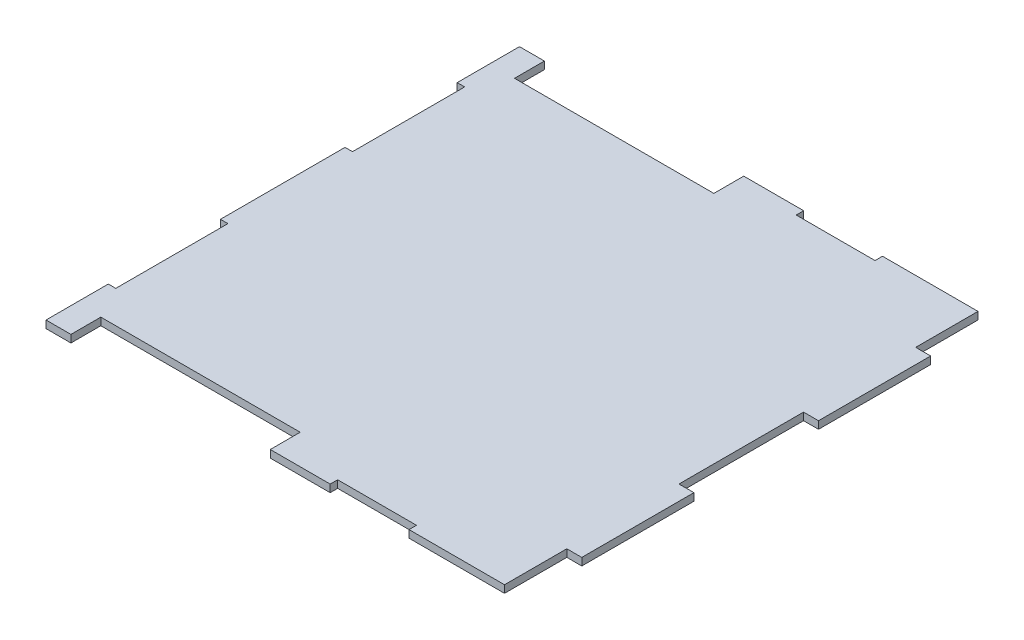
SolidWorks part; units mm, degrees
ref_plane "Front Plane" through (0, 0, 0) normal (0, 0, 1) x (1, 0, 0)
ref_plane "Top Plane" through (0, 0, 0) normal (0, 1, 0) x (1, 0, 0)
ref_plane "Right Plane" through (0, 0, 0) normal (1, 0, 0) x (0, 0, -1)
sketch "Sketch1" plane through (0, 0, 0) normal (0, 1, 0) x (1, 0, 0)
  line L1 (-95, -95) -> (95, -95)
  line L2 (-95, -95) -> (-95, 95)
  line L3 (-95, 95) -> (95, 95)
  line L4 (95, -95) -> (95, 95)
  line L5 (-95, -95) -> (95, 95) construction
  line L6 (-95, 95) -> (95, -95) construction
  point P0 (0, 0)
  dimension "D1" = 190
  dimension "D2" = 190
extrude "Boss-Extrude1" add sketch "Sketch1" along normal blind 3
sketch "Sketch2" plane through (0, 3, 0) normal (0, 1, 0) x (1, 0, 0)
  line L0 (-95, -95) -> (-95, -70)
  line L1 (-95, 95) -> (-95, -95) construction
  line L2 (-95, -70) -> (-92, -70)
  line L3 (-92, -70) -> (-92, -25)
  line L4 (-92, -25) -> (-95, -25)
  line L5 (-95, -25) -> (-95, 25)
  line L6 (89, 95) -> (89, 70)
  line L7 (-92, 25) -> (-95, 25)
  line L8 (-92, 70) -> (-92, 25)
  line L9 (-95, 70) -> (-92, 70)
  line L10 (-95, 95) -> (-95, 70)
  line L11 (0, -1000) -> (0, 49000) construction
  line L21 (-95, -95) -> (89, -95)
  line L22 (-95, 95) -> (89, 95)
  line L23 (89, 70) -> (95, 70)
  line L24 (95, -95) -> (95, 95) construction
  line L26 (95, 70) -> (95, 25)
  line L27 (95, 25) -> (89, 25)
  line L29 (89, 25) -> (89, -25)
  line L30 (89, -25) -> (95, -25)
  line L31 (95, -25) -> (95, -70)
  line L33 (95, -70) -> (89, -70)
  line L34 (89, -70) -> (89, -95)
  point P13 (-95, 0)
  dimension "D1" = 25
  dimension "D2" = 25
  dimension "D3" = 3
  dimension "D4" = 6
  dimension "D5" = 6
  dimension "D6" = 6
extrude "Cut-Extrude2" cut sketch "Sketch2" against normal blind 3 and the other way through all flip side to cut
sketch "Sketch4" plane through (0, 3, 0) normal (0, 1, 0) x (1, 0, 0)
  line L0 (89, 95) -> (-95, 95) construction
  line L1 (-85, 83) -> (-5, 83)
  line L2 (-85, 83) -> (-85, 95)
  line L3 (-85, 95) -> (-5, 95)
  line L4 (-5, 83) -> (-5, 95)
  line L5 (-85, 83) -> (-5, 95) construction
  line L6 (-85, 95) -> (-5, 83) construction
  line L7 (-95, 95) -> (-95, 70) construction
  line L8 (-1000, 0) -> (49000, 0) construction
  line L9 (-85, -95) -> (-5, -83) construction
  line L10 (-85, -83) -> (-5, -95) construction
  line L11 (-5, -83) -> (-5, -95)
  line L12 (-85, -95) -> (-5, -95)
  line L13 (-85, -83) -> (-85, -95)
  line L14 (-85, -83) -> (-5, -83)
  point P0 (-45, 89)
  point P7 (-45, 83)
  point P17 (-45, -89)
  dimension "D1" = 80
  dimension "D2" = 12
  dimension "D3" = 50
extrude "Cut-Extrude4" cut sketch "Sketch4" against normal blind 3
sketch "Sketch5" plane through (0, 0, 95) normal (0, 0, 1) x (1, 0, 0)
  line L0 (50.6784, 3) -> (50.6929, 0)
  line L1 (-5, 3) -> (89, 3) construction
  line L2 (-5, 0) -> (89, 0) construction
  line L3 (50.6929, 0) -> (19.0397, 0)
  line L4 (19.0397, 0) -> (19.0397, 3)
  line L5 (19.0397, 3) -> (50.6784, 3)
extrude "Cut-Extrude5" cut sketch "Sketch5" against normal blind 3
mirror "Mirror1" about plane through (0, 0, 0) normal (0, 0, 1) of "Cut-Extrude5"
